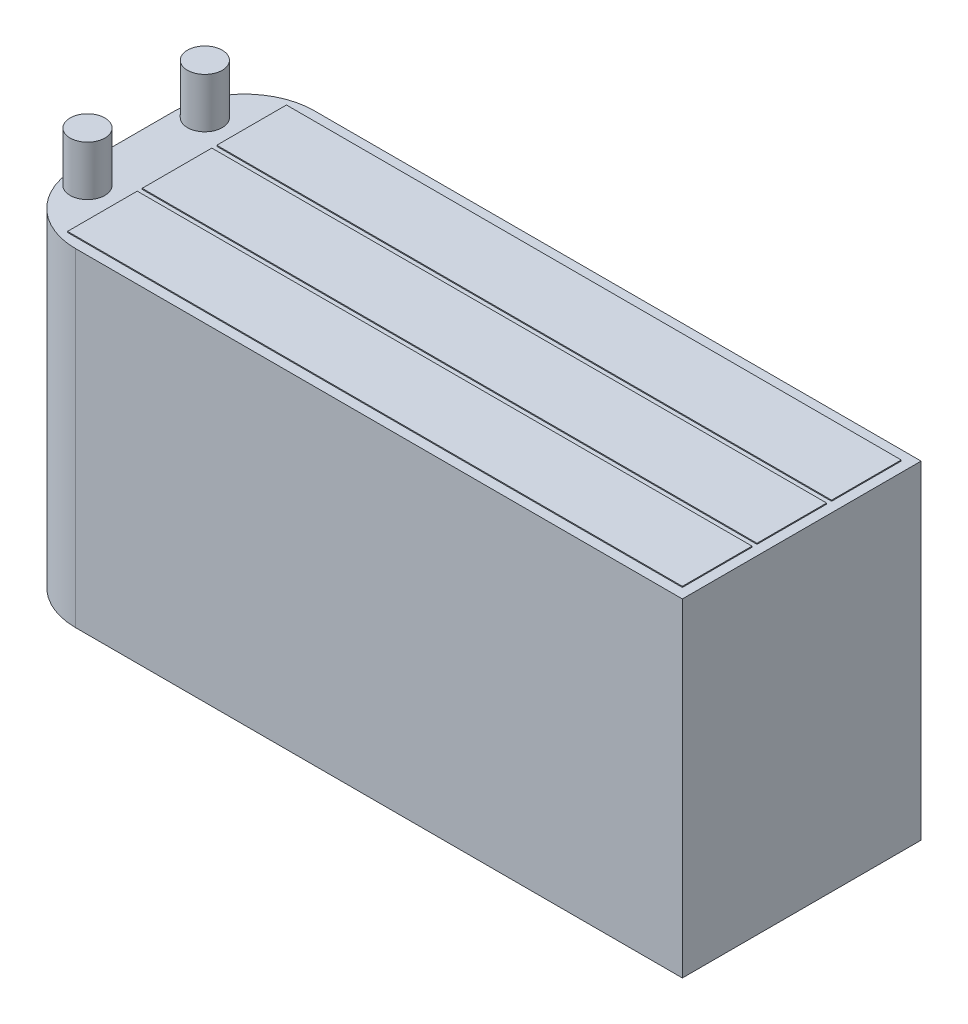
SolidWorks part; units mm, degrees
ref_plane "Front Plane" through (0, 0, 0) normal (0, 0, 1) x (1, 0, 0)
ref_plane "Top Plane" through (0, 0, 0) normal (0, 1, 0) x (1, 0, 0)
ref_plane "Right Plane" through (0, 0, 0) normal (1, 0, 0) x (0, 0, -1)
sketch "Sketch1" plane through (0, 0, 0) normal (0, 0, 1) x (1, 0, 0)
  line L1 (-34, -16.5) -> (34, -16.5)
  line L2 (-34, -16.5) -> (-34, 16.5)
  line L3 (-34, 16.5) -> (34, 16.5)
  line L4 (34, -16.5) -> (34, 16.5)
  line L5 (-34, -16.5) -> (34, 16.5) construction
  line L6 (-34, 16.5) -> (34, -16.5) construction
  point P0 (0, 0)
  dimension "D1" = 68
  dimension "D2" = 33
extrude "Boss-Extrude1" add sketch "Sketch1" along normal blind 24
fillet "Fillet1" radius 7 2 edges at (-34, 0, 0) (-34, 0, 24)
sketch "Sketch2" plane through (0, 16.5, 0) normal (0, 1, 0) x (1, 0, 0)
  line L0 (33, -19.5) -> (34, -19.5) construction
  line L1 (33, -1) -> (-28.8, -1)
  line L2 (33, -1) -> (33, -8)
  line L3 (33, -8) -> (-28.8, -8)
  line L4 (-28.8, -1) -> (-28.8, -8)
  line L5 (33, -8.5) -> (-28.8, -8.5)
  line L6 (33, -8.5) -> (33, -15.5)
  line L7 (33, -15.5) -> (-28.8, -15.5)
  line L8 (-28.8, -8.5) -> (-28.8, -15.5)
  line L9 (-28.8, -16) -> (33, -16)
  line L10 (-28.8, -16) -> (-28.8, -23)
  line L11 (-28.8, -23) -> (33, -23)
  line L12 (33, -16) -> (33, -23)
  line L13 (34, -24) -> (34, 0) construction
  line L14 (33, -12) -> (34, -12) construction
  line L15 (33, -4.5) -> (34, -4.5) construction
  line L16 (34, -4.5) -> (34, -12) construction
  line L17 (34, -12) -> (34, -19.5) construction
  line L18 (2.1, -8.5) -> (2.1, -8) construction
  line L19 (2.1, -15.5) -> (2.1, -16) construction
  line L20 (2.1, -1) -> (2.1, 0) construction
  line L21 (34, 0) -> (-27, 0) construction
  line L22 (2.1, -23) -> (2.1, -24) construction
  line L23 (34, -24) -> (-27, -24) construction
  dimension "D1" = 0.5
  dimension "D2" = 1
  dimension "D3" = 1
extrude "Boss-Extrude2" add sketch "Sketch2" along normal blind 0.1 separate body
mirror "Mirror1" about plane through (0, 0, 0) normal (0, 1, 0) of bodies 115 120 119 117
sketch "Sketch3" plane through (0, 16.5, 0) normal (0, 1, 0) x (1, 0, 0)
  line L0 (-31.9, -6.1) -> (-31.9, -17.9) construction
  line L1 (-34, -12) -> (-31.9, -12) construction
  line L2 (-34, -17) -> (-34, -7) construction
  circle A0 centre (-31.9, -6.1) radius 1.75
  circle A1 centre (-31.9, -17.9) radius 1.75
  point P8 (-31.1, -7.4)
  point P9 (-31.9, -6.9)
  point P10 (-31.9, -6.1)
  dimension "D1" = 3.5
extrude "Boss-Extrude3" add sketch "Sketch3" along normal blind 5
